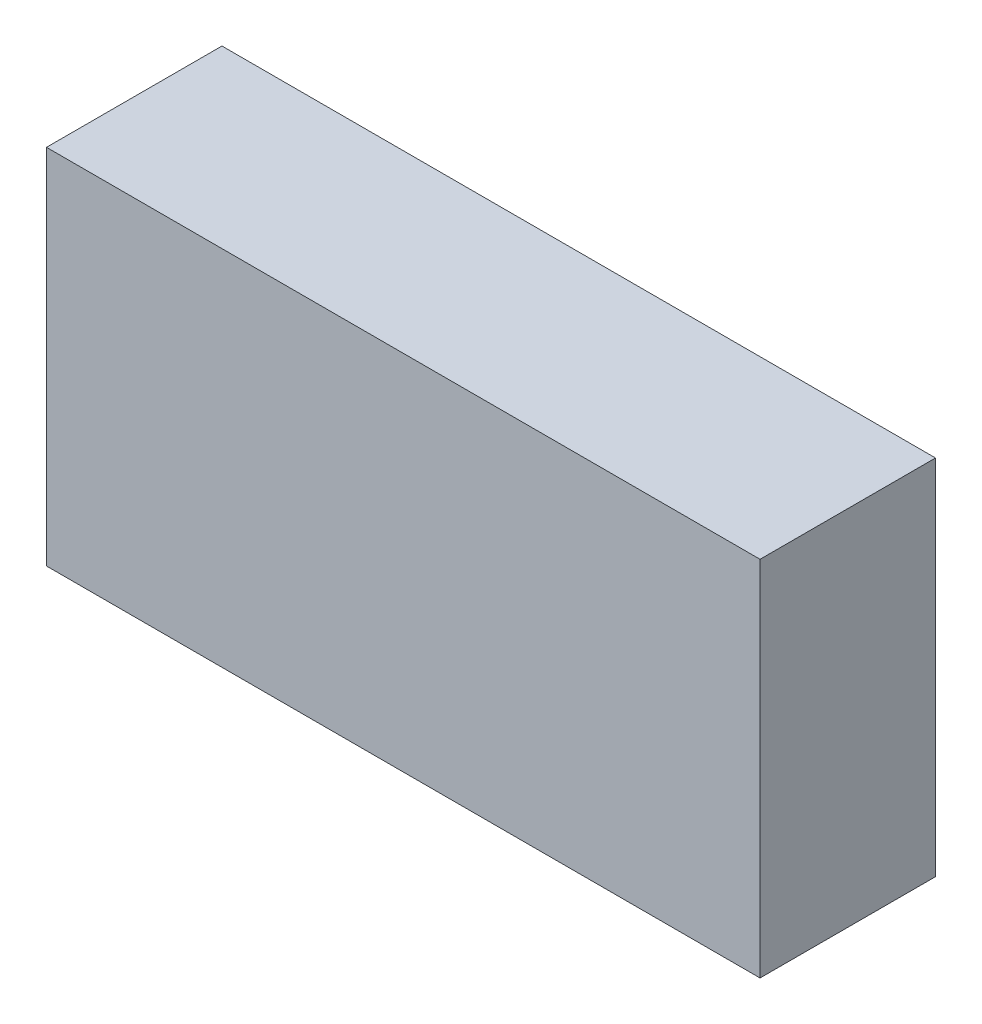
SolidWorks part; units mm, degrees
ref_plane "Front Plane" through (0, 0, 0) normal (0, 0, 1) x (1, 0, 0)
ref_plane "Top Plane" through (0, 0, 0) normal (0, 1, 0) x (1, 0, 0)
ref_plane "Right Plane" through (0, 0, 0) normal (1, 0, 0) x (0, 0, -1)
sketch "Sketch1" plane through (0, 0, 0) normal (0, 0, 1) x (1, 0, 0)
  line L0 (0, 44.7617) -> (0, -42.4439) construction
  line L1 (-67.0701, 0) -> (65.9112, 0) construction
  line L2 (30.5, 15.5) -> (-30.5, 15.5)
  line L3 (-30.5, 15.5) -> (-30.5, -15.5)
  line L4 (30.5, -15.5) -> (-30.5, -15.5)
  line L5 (30.5, 15.5) -> (30.5, -15.5)
  point P9 (-30.5, 0)
  point P10 (30.5, 0)
  point P12 (0, -15.5)
  point P13 (0, 15.5)
  dimension "D1" = 31
  dimension "D2" = 61
extrude "Boss-Extrude1" add sketch "Sketch1" along normal blind 15
